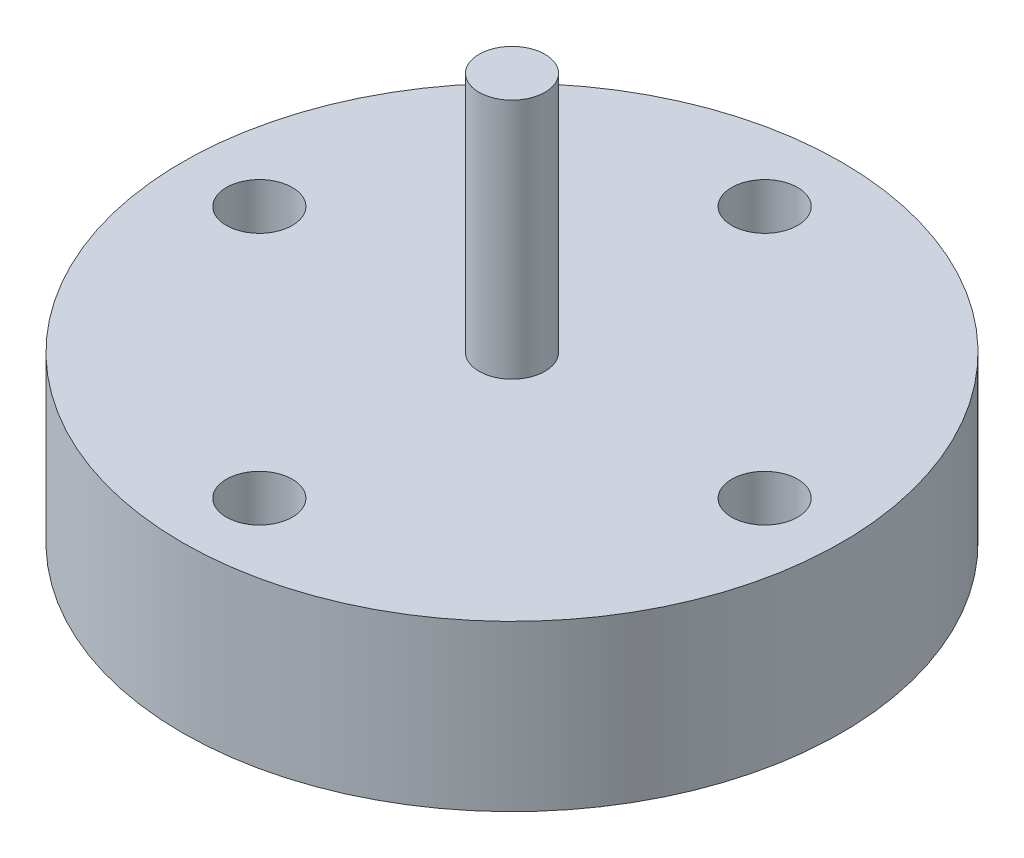
SolidWorks part; units mm, degrees
ref_plane "Front Plane" through (0, 0, 0) normal (0, 0, 1) x (1, 0, 0)
ref_plane "Top Plane" through (0, 0, 0) normal (0, 1, 0) x (1, 0, 0)
ref_plane "Right Plane" through (0, 0, 0) normal (1, 0, 0) x (0, 0, -1)
sketch "Sketch1" plane through (0, 0, 0) normal (0, 1, 0) x (1, 0, 0)
  circle A0 centre (0, 0) radius 15
  dimension "D1" = 30
extrude "Boss-Extrude1" add sketch "Sketch1" along normal blind 7.5
sketch "Sketch2" plane through (0, 7.5, 0) normal (0, 1, 0) x (1, 0, 0)
  circle A0 centre (0, 0) radius 1.5
  dimension "D1" = 3
extrude "Boss-Extrude2" add sketch "Sketch2" along normal blind 11
sketch "Sketch4" plane through (0, 0, 0) normal (0, -1, 0) x (1, 0, 0)
  circle A0 centre (0, 0) radius 7.5
  dimension "D1" = 15
extrude "Cut-Extrude3" cut sketch "Sketch4" against normal blind 3.5
sketch "Sketch6" plane through (0, 7.5, 0) normal (0, 1, 0) x (1, 0, 0)
  circle A0 centre (0, 0) radius 11.5 construction
  circle A1 centre (0, 11.5) radius 1.5
  circle A2 centre (11.5, 0) radius 1.5
  circle A3 centre (0, -11.5) radius 1.5
  circle A4 centre (-11.5, 0) radius 1.5
  dimension "D1" = 23
  dimension "D2" = 3
extrude "Cut-Extrude4" cut sketch "Sketch6" against normal through all
